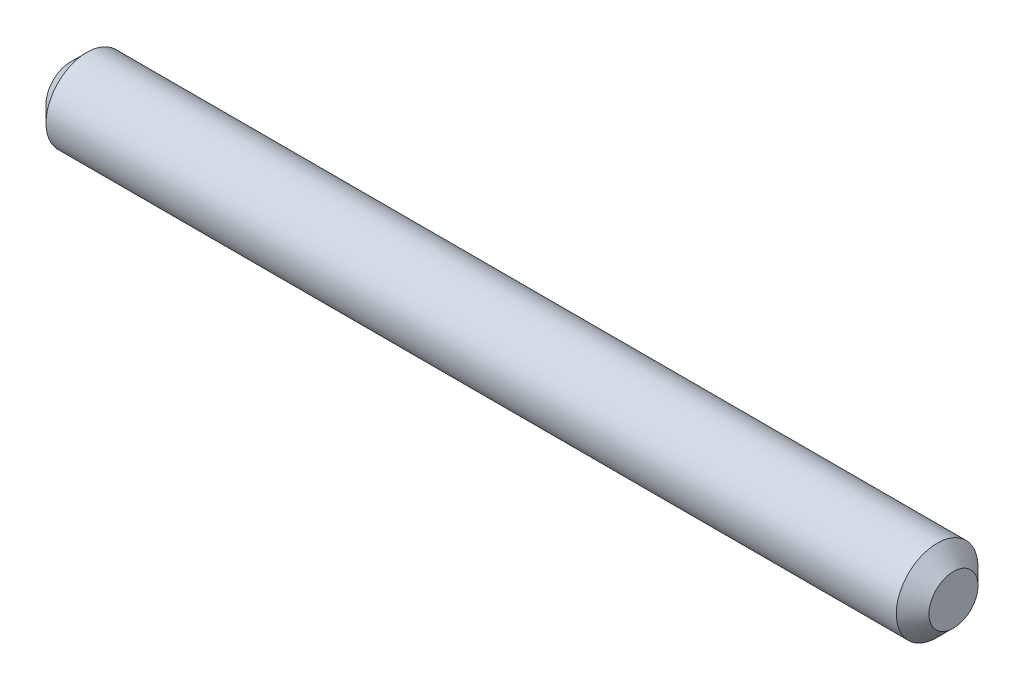
SolidWorks part; units mm, degrees
ref_plane "Front Plane" through (0, 0, 0) normal (0, 0, 1) x (1, 0, 0)
ref_plane "Top Plane" through (0, 0, 0) normal (0, 1, 0) x (1, 0, 0)
ref_plane "Right Plane" through (0, 0, 0) normal (1, 0, 0) x (0, 0, -1)
sketch "Sketch1" plane through (0, 0, 0) normal (0, 0, 1) x (1, 0, 0)
  line L0 (-26.0823, 0) -> (76.4362, 0) construction
  line L1 (-11.1752, 0) -> (-11.1752, 1.5)
  line L2 (-11.1752, 1.5) -> (-10.1752, 2.5)
  line L3 (-10.1752, 2.5) -> (41.8248, 2.5)
  line L4 (41.8248, 2.5) -> (42.8248, 1.5)
  line L5 (42.8248, 1.5) -> (42.8248, 0)
  line L6 (-11.1752, 0) -> (42.8248, 0)
  point P5 (0, 0)
  point P10 (76.4362, 0)
  dimension "D1" = 1
  dimension "D2" = 2.5
  dimension "D3" = 45
  dimension "D4" = 45
  dimension "D5" = 1
  dimension "D6" = 54
revolve "Revolve1" add sketch "Sketch1" angle 360 about L0
